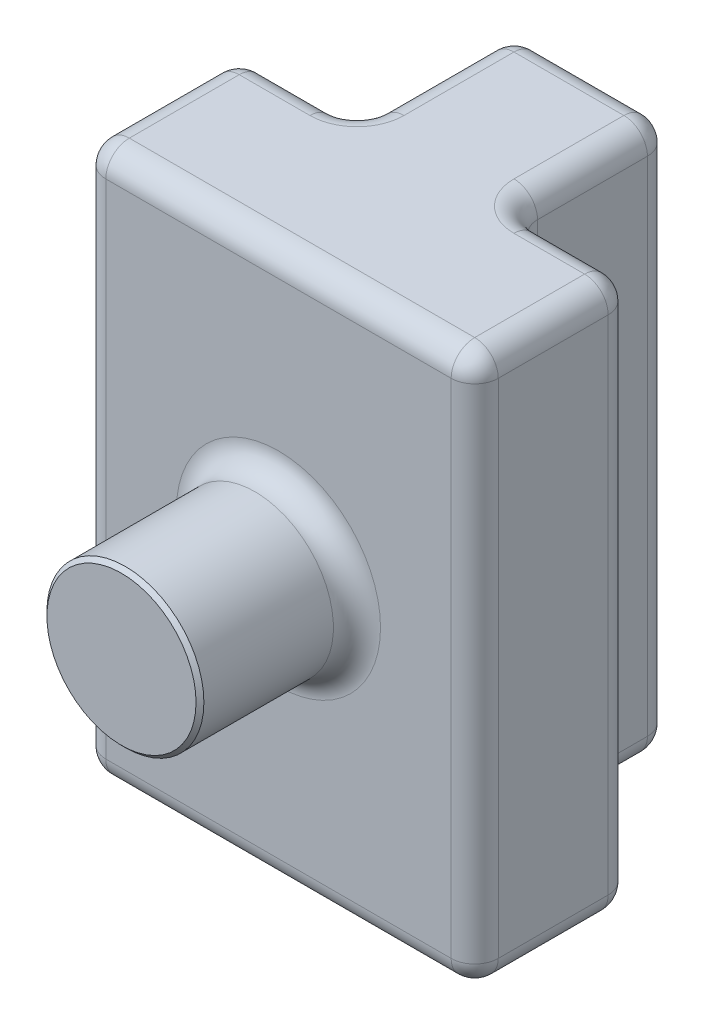
SolidWorks part; units mm, degrees
ref_plane "Front Plane" through (0, 0, 0) normal (0, 0, 1) x (1, 0, 0)
ref_plane "Top Plane" through (0, 0, 0) normal (0, 1, 0) x (1, 0, 0)
ref_plane "Right Plane" through (0, 0, 0) normal (1, 0, 0) x (0, 0, -1)
sketch "Sketch1" plane through (0, 0, 0) normal (0, 1, 0) x (1, 0, 0)
  line L0 (25, 0) -> (-25, 0)
  line L1 (-25, 0) -> (-25, 20)
  line L2 (-25, 20) -> (-10, 20)
  line L3 (-10, 20) -> (-10, 40)
  line L4 (-10, 40) -> (10, 40)
  line L5 (10, 40) -> (10, 20)
  line L6 (10, 20) -> (25, 20)
  line L7 (25, 20) -> (25, 0)
  point P4 (0, 0)
  point P11 (0, 40)
  dimension "D1" = 20
  dimension "D2" = 50
  dimension "D3" = 20
  dimension "D4" = 20
  dimension "D5" = 15
extrude "Boss-Extrude1" add sketch "Sketch1" along normal mid plane 70
sketch "Sketch2" plane through (0, 0, 0) normal (0, 0, 1) x (1, 0, 0)
  circle A0 centre (0, 0) radius 10
  dimension "D1" = 20
extrude "Boss-Extrude2" add sketch "Sketch2" along normal blind 20
fillet "Fillet1" radius 3 25 edges at (25, 0, -20) (-25, -35, -10) (25, -35, -10) (17.5, -35, -20) (-10, -35, -30) (-10, 0, -20) (-25, 0, -20) (-17.5, -35, -20) (-10, 0, -40) (0, -35, -40) (10, 0, -20) (10, 0, -40) (10, -35, -30) (-10, 35, -30) (0, 35, -40) (10, 35, -30) (17.5, 35, -20) (25, 35, -10) (-25, 35, -10) (-17.5, 35, -20) (-25, 0, 0) (0, 35, 0) (25, 0, 0) (0, -35, 0) (10, 0, 0)
chamfer "Chamfer1" distance 0.5 angle 45 1 edges at (10, 0, 20)
